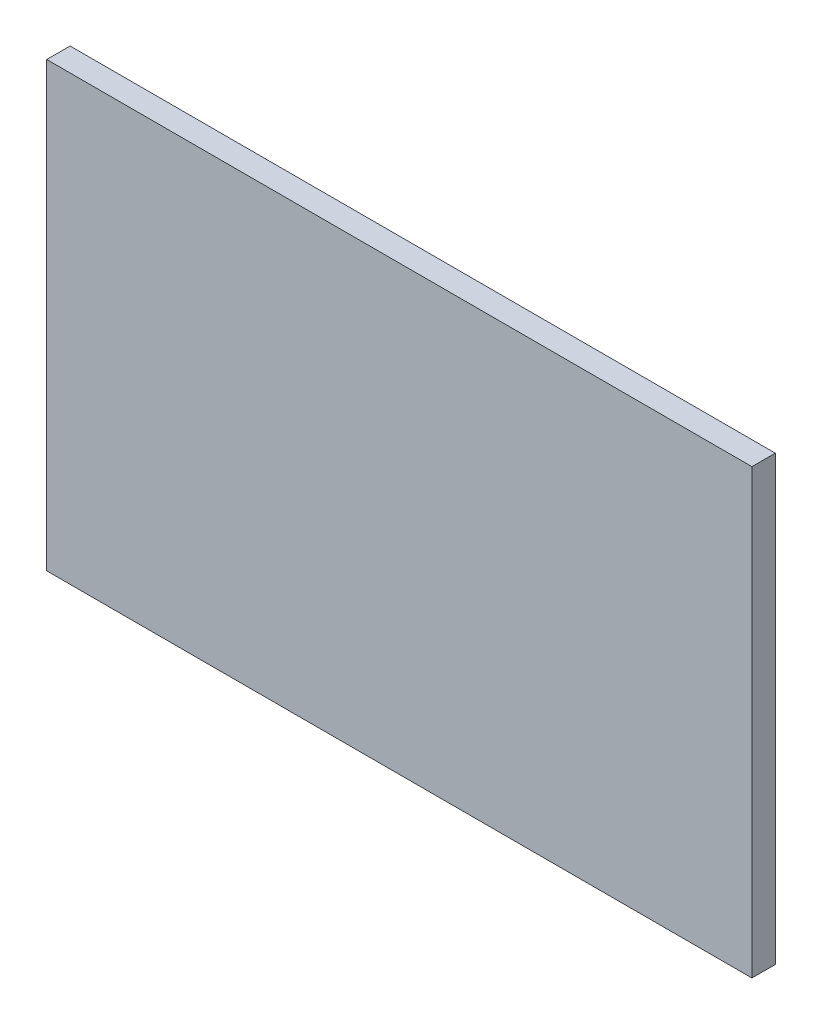
SolidWorks part; units mm, degrees
ref_plane "前视基准面" through (0, 0, 0) normal (0, 0, 1) x (1, 0, 0)
ref_plane "上视基准面" through (0, 0, 0) normal (0, 1, 0) x (1, 0, 0)
ref_plane "右视基准面" through (0, 0, 0) normal (1, 0, 0) x (0, 0, -1)
other "Configuration Table"
sketch "草图1" plane through (0, 0, 118.0175) normal (0, 0, -1) x (-1, 0, 0)
  line L0 (-51.6217, 40.0354) -> (69.0659, -35.9521) construction
  line L1 (69.0532, 40.0354) -> (-51.6217, -35.9394) construction
  line L3 (69.0721, 39.9416) -> (-51.6279, 39.9416)
  line L4 (69.0721, 39.9416) -> (69.0721, -35.8584)
  line L5 (69.0721, -35.8584) -> (-51.6279, -35.8584)
  line L6 (-51.6279, 39.9416) -> (-51.6279, -35.8584)
  line L7 (69.0721, 39.9416) -> (-51.6279, -35.8584) construction
  line L8 (69.0721, -35.8584) -> (-51.6279, 39.9416) construction
  point P8 (8.7221, 2.0416)
  dimension "D1" = 120.7
  dimension "D2" = 75.8
extrude "凸台-拉伸1" add sketch "草图1" along normal blind 4
